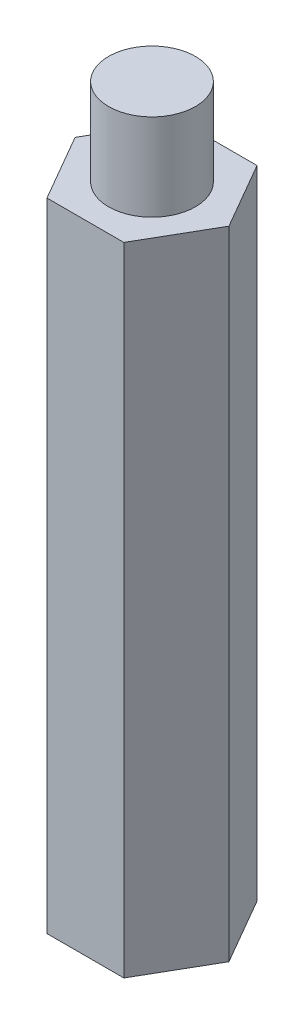
SolidWorks part; units mm, degrees
ref_plane "Front Plane" through (0, 0, 0) normal (0, 0, 1) x (1, 0, 0)
ref_plane "Top Plane" through (0, 0, 0) normal (0, 1, 0) x (1, 0, 0)
ref_plane "Right Plane" through (0, 0, 0) normal (1, 0, 0) x (0, 0, -1)
other "Configuration Table"
sketch "草图1" plane through (0, 0, 0) normal (0, 1, 0) x (1, 0, 0)
  line L1 (2.6558, 0) -> (1.3279, 2.3)
  line L2 (1.3279, 2.3) -> (-1.3279, 2.3)
  line L3 (-1.3279, 2.3) -> (-2.6558, 0)
  line L4 (-2.6558, 0) -> (-1.3279, -2.3)
  line L5 (-1.3279, -2.3) -> (1.3279, -2.3)
  line L6 (1.3279, -2.3) -> (2.6558, 0)
  circle A0 centre (0, 0) radius 2.3 construction
extrude "凸台-拉伸1" add sketch "草图1" along normal blind 22
sketch "草图2" plane through (0, 22, 0) normal (0, 1, 0) x (1, 0, 0)
  circle A0 centre (0, 0) radius 1.5
extrude "凸台-拉伸2" add sketch "草图2" along normal blind 3
sketch "草图3" plane through (0, 0, 0) normal (0, -1, 0) x (-1, 0, 0)
  circle A0 centre (0, 0) radius 1.5
extrude "切除-拉伸1" cut sketch "草图3" against normal blind 3
